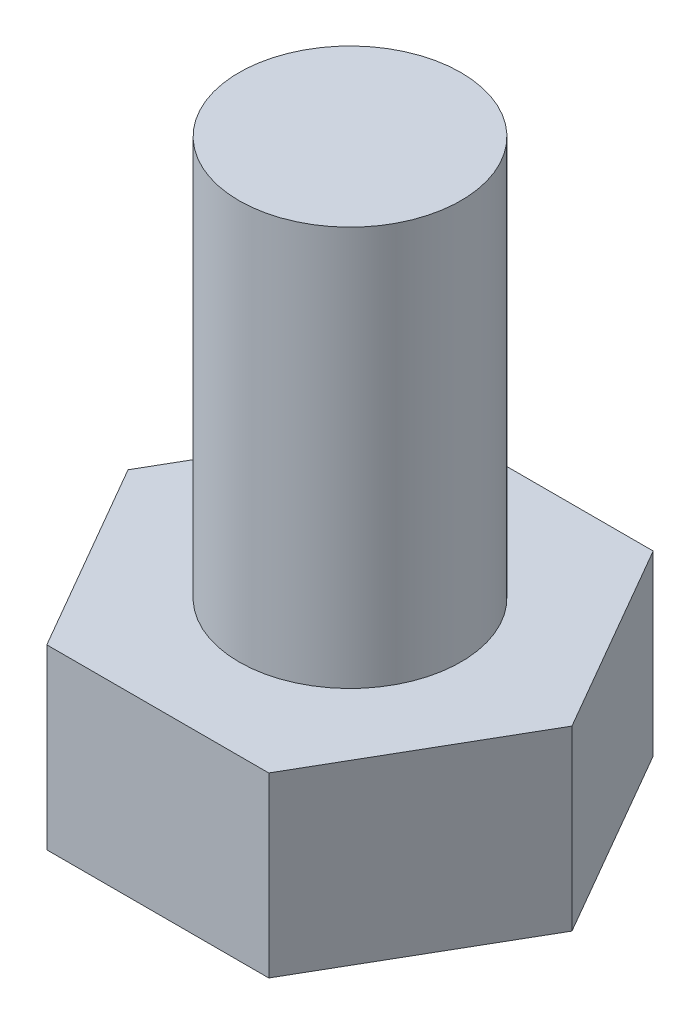
SolidWorks part; units mm, degrees
ref_plane "Front Plane" through (0, 0, 0) normal (0, 0, 1) x (1, 0, 0)
ref_plane "Top Plane" through (0, 0, 0) normal (0, 1, 0) x (1, 0, 0)
ref_plane "Right Plane" through (0, 0, 0) normal (1, 0, 0) x (0, 0, -1)
sketch "Sketch1" plane through (0, 0, 0) normal (0, 1, 0) x (1, 0, 0)
  circle A0 centre (0, 0) radius 2.5
  dimension "D1" = 5
extrude "Boss-Extrude1" add sketch "Sketch1" along normal blind 13
sketch "Sketch2" plane through (0, 0, 0) normal (0, 1, 0) x (1, 0, 0)
  line L1 (2.5, -4.3301) -> (5, 0)
  line L2 (5, 0) -> (2.5, 4.3301)
  line L3 (2.5, 4.3301) -> (-2.5, 4.3301)
  line L4 (-2.5, 4.3301) -> (-5, 0)
  line L5 (-5, 0) -> (-2.5, -4.3301)
  line L6 (-2.5, -4.3301) -> (2.5, -4.3301)
  circle A0 centre (0, 0) radius 4.3301 construction
  circle A2 centre (0, 0) radius 2.5
  circle A3 centre (0, 0) radius 2.5
  dimension "D1" = 10
  dimension "D2" = 0
extrude "Boss-Extrude2" add sketch "Sketch2" along normal blind 4
